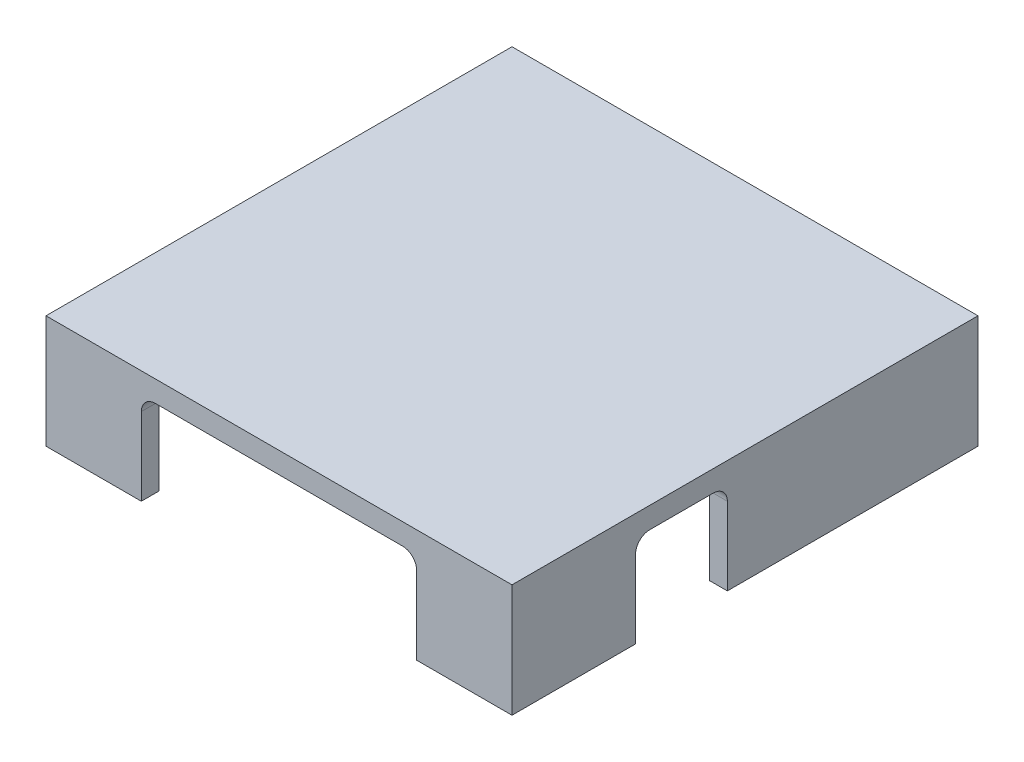
SolidWorks part; units mm, degrees
ref_plane "Front Plane" through (0, 0, 0) normal (0, 0, 1) x (1, 0, 0)
ref_plane "Top Plane" through (0, 0, 0) normal (0, 1, 0) x (1, 0, 0)
ref_plane "Right Plane" through (0, 0, 0) normal (1, 0, 0) x (0, 0, -1)
sketch "Sketch1" plane through (0, 0, 0) normal (0, 1, 0) x (1, 0, 0)
  line L0 (-55, 0) -> (55, 0) construction
  line L1 (-33, 33) -> (33, 33)
  line L2 (-33, 33) -> (-33, -33)
  line L3 (-33, -33) -> (33, -33)
  line L4 (33, 33) -> (33, -33)
  line L5 (0, -55) -> (0, 55) construction
  dimension "D1" = 33
  dimension "D2" = 66
  dimension "D3" = 66
  dimension "D4" = 33
extrude "Boss-Extrude1" add sketch "Sketch1" along normal blind 3
sketch "Sketch2" plane through (0, 0, 0) normal (0, 1, 0) x (1, 0, 0)
  line L0 (0, -1.65) -> (0, 1.65) construction
  line L1 (-30.5, 30.5) -> (-14.5, 30.5)
  line L2 (-30.5, 30.5) -> (-30.5, 9.5)
  line L3 (-30.5, -30.5) -> (-19.5, -30.5)
  line L4 (30.5, 30.5) -> (30.5, -2.5)
  line L5 (-1.65, 0) -> (1.65, 0) construction
  line L6 (-14.5, 33) -> (-14.5, 30.5)
  line L7 (33, 33) -> (-33, 33) construction
  line L8 (-4.5, 33) -> (6.5, 33)
  line L9 (-4.5, 33) -> (-4.5, 30.5)
  line L10 (6.5, 30.5) -> (6.5, 33)
  line L11 (16.5, 33) -> (33, 33)
  line L12 (16.5, 33) -> (16.5, 30.5)
  line L13 (-4.5, 30.5) -> (6.5, 30.5)
  line L14 (16.5, 30.5) -> (30.5, 30.5)
  line L15 (30.5, -15.5) -> (33, -15.5)
  line L16 (33, -33) -> (33, 33) construction
  line L17 (33, -2.5) -> (33, 33)
  line L18 (33, -2.5) -> (30.5, -2.5)
  line L19 (30.5, -15.5) -> (30.5, -30.5)
  line L20 (19.5, -30.5) -> (19.5, -33)
  line L21 (-33, -33) -> (33, -33) construction
  line L22 (19.5, -33) -> (33, -33)
  line L23 (-19.5, -33) -> (-19.5, -30.5)
  line L24 (19.5, -30.5) -> (30.5, -30.5)
  line L25 (-30.5, 9.5) -> (-33, 9.5)
  line L26 (-33, 33) -> (-33, -33) construction
  line L27 (-33, 9.5) -> (-33, 33)
  line L28 (-33, -18.5) -> (-30.5, -18.5)
  line L29 (-30.5, -18.5) -> (-30.5, -30.5)
  line L31 (-33, -33) -> (-19.5, -33)
  line L32 (-33, -33) -> (-33, -18.5)
  line L33 (-33, 33) -> (-14.5, 33)
  line L34 (33, -33) -> (33, -15.5)
  dimension "D1" = 30.5
  dimension "D2" = 30.5
  dimension "D3" = 30.5
  dimension "D4" = 30.5
  dimension "D5" = 16
  dimension "D6" = 10
  dimension "D7" = 14
  dimension "D8" = 10
  dimension "D9" = 28
  dimension "D10" = 13
  dimension "D11" = 11
  dimension "D12" = 11
  dimension "D13" = 40
  dimension "D14" = 28
extrude "Boss-Extrude3" add sketch "Sketch2" against normal blind 13
sketch "Sketch5" plane through (30.5, 0, 0) normal (-1, 0, 0) x (0, 0, 1)
  line L0 (-30.5, -13) -> (2.5, -13) construction
  line L1 (-14.5, -13) -> (-4.5, -13)
  line L2 (-14.5, -13) -> (-14.5, -11.5)
  line L3 (-14.5, -11.5) -> (-4.5, -11.5)
  line L4 (-4.5, -13) -> (-4.5, -11.5)
  line L5 (-30.5, -13) -> (-30.5, 0) construction
  dimension "D1" = 16
  dimension "D2" = 10
  dimension "D3" = 1.5
extrude "Boss-Extrude4" add sketch "Sketch5" along normal blind 1.5
fillet "Fillet2" radius 1 1 edges at (29, -13, -9.5)
sketch "Sketch6" plane through (-30.5, 0, 0) normal (1, 0, 0) x (0, 0, -1)
  line L0 (9.5, -13) -> (30.5, -13) construction
  line L1 (22.5, -13) -> (12.5, -13)
  line L2 (22.5, -13) -> (22.5, -11.5)
  line L3 (22.5, -11.5) -> (12.5, -11.5)
  line L4 (12.5, -13) -> (12.5, -11.5)
  line L5 (30.5, -13) -> (30.5, 0) construction
  dimension "D1" = 8
  dimension "D2" = 10
  dimension "D3" = 1.5
extrude "Boss-Extrude5" add sketch "Sketch6" along normal blind 1.5
fillet "Fillet3" radius 1 1 edges at (-29, -13, -17.5)
fillet "Fillet4" radius 2 19 edges at (31.75, 0, 15.5) (-31.75, 0, 18.5) (19.5, 0, 31.75) (-4.5, 0, -31.75) (31.75, 0, 2.5) (-19.5, 0, 31.75) (6.5, 0, -31.75) (16.5, 0, -31.75) (25, 0, 30.5) (-25, 0, 30.5) (-30.5, 0, 24.5) (30.5, 0, 23) (30.5, 0, -14) (23.5, 0, -30.5) (1, 0, -30.5) (-22.5, 0, -30.5) (-30.5, 0, -20)
